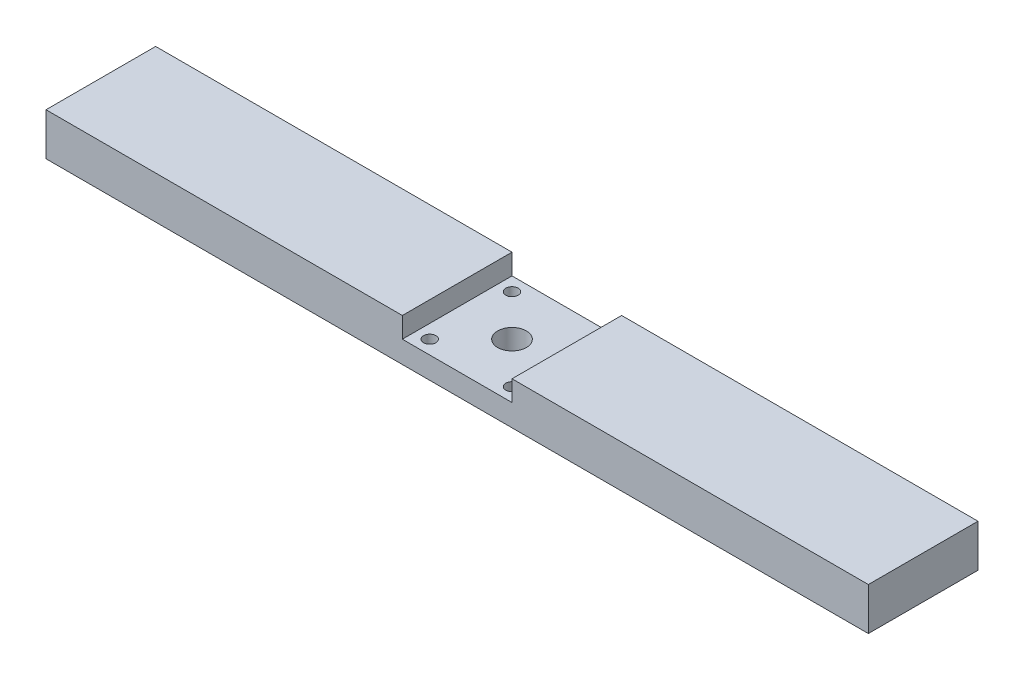
SolidWorks part; units mm, degrees
ref_plane "Front Plane" through (0, 0, 0) normal (0, 0, 1) x (1, 0, 0)
ref_plane "Top Plane" through (0, 0, 0) normal (0, 1, 0) x (1, 0, 0)
ref_plane "Right Plane" through (0, 0, 0) normal (1, 0, 0) x (0, 0, -1)
sketch "Sketch1" plane through (0, 0, 0) normal (0, 0, 1) x (1, 0, 0)
  line L0 (0, 104.1848) -> (0, -100.9565) construction
  line L1 (-150, 7.75) -> (-150, -7.75)
  line L2 (-150, -7.75) -> (150, -7.75)
  line L3 (-150, 7.75) -> (-20, 7.75)
  line L4 (-20, 7.75) -> (-20, 0.25)
  line L5 (-20, 0.25) -> (20, 0.25)
  line L6 (150, 7.75) -> (150, -7.75)
  line L7 (20, 7.75) -> (20, 0.25)
  line L8 (150, 7.75) -> (20, 7.75)
  point P5 (-150, 0)
  point P12 (0, -7.75)
  point P14 (0, 0.25)
  dimension "D1" = 300
  dimension "D2" = 15.5
  dimension "D3" = 7.5
  dimension "D4" = 40
extrude "Boss-Extrude1" add sketch "Sketch1" along normal mid plane 40
sketch "Sketch2" plane through (0, 0.25, 0) normal (0, 1, 0) x (1, 0, 0)
  line L0 (-3.5, 3.5) -> (-1.225, 3.5) construction
  line L1 (-3.5, 10) -> (3.5, 10) construction
  line L2 (-3.5, 10) -> (-3.5, 3.5) construction
  line L3 (-3.5, -10) -> (3.5, -10) construction
  line L4 (3.5, 10) -> (3.5, 3.5) construction
  line L5 (-3.5, 10) -> (3.5, -10) construction
  line L6 (-3.5, -10) -> (3.5, 10) construction
  line L7 (-10, 3.5) -> (-3.5, 3.5) construction
  line L8 (-10, 3.5) -> (-10, -3.5) construction
  line L9 (-10, -3.5) -> (-3.5, -3.5) construction
  line L10 (10, 3.5) -> (10, -3.5) construction
  line L11 (-10, 3.5) -> (10, -3.5) construction
  line L12 (-10, -3.5) -> (10, 3.5) construction
  line L13 (-1.225, 3.5) -> (1.225, 3.5) construction
  line L14 (-3.5, 3.5) -> (-3.5, 1.225) construction
  line L15 (-3.5, -3.5) -> (-3.5, -10) construction
  line L16 (-3.5, 1.225) -> (-3.5, -1.225) construction
  line L17 (-3.5, -1.225) -> (-3.5, -3.5) construction
  line L18 (-3.5, -3.5) -> (-1.225, -3.5) construction
  line L19 (3.5, -3.5) -> (10, -3.5) construction
  line L20 (-1.225, -3.5) -> (1.225, -3.5) construction
  line L21 (1.225, -3.5) -> (3.5, -3.5) construction
  line L22 (3.5, -1.225) -> (3.5, -3.5) construction
  line L23 (3.5, -3.5) -> (3.5, -10) construction
  line L24 (3.5, 1.225) -> (3.5, -1.225) construction
  line L25 (3.5, 3.5) -> (3.5, 1.225) construction
  line L26 (1.225, 3.5) -> (3.5, 3.5) construction
  line L27 (3.5, 3.5) -> (10, 3.5) construction
  line L28 (0, 16.757) -> (0, -13.5066) construction
  line L29 (-13.5311, 0) -> (11.9505, 0) construction
  line L31 (0, -9.815) -> (8.5, -4.9075) construction
  line L32 (8.5, -4.9075) -> (8.5, 4.9075) construction
  line L33 (8.5, 4.9075) -> (0, 9.815) construction
  line L34 (0, 9.815) -> (-8.5, 4.9075) construction
  line L35 (-8.5, 4.9075) -> (-8.5, -4.9075) construction
  line L36 (-8.5, -4.9075) -> (0, -9.815) construction
  circle A0 centre (15.015, 15) radius 2.25
  circle A1 centre (-15.015, 15) radius 2.25
  circle A2 centre (15.015, -15) radius 2.25
  circle A3 centre (-15.015, -15) radius 2.25
  circle A4 centre (0, 0) radius 8.5 construction
  circle A5 centre (0, 0) radius 5.25
  point P0 (0, 0)
  point P5 (0, 0)
  dimension "D5" = 15
  dimension "D7" = 4.5
  dimension "D9" = 10.5
  dimension "D1" = 7
  dimension "D2" = 20
  dimension "D3" = 7
  dimension "D4" = 20
  dimension "D6" = 15.015
  dimension "D8" = 17
extrude "Cut-Extrude1" cut sketch "Sketch2" against normal blind 40
